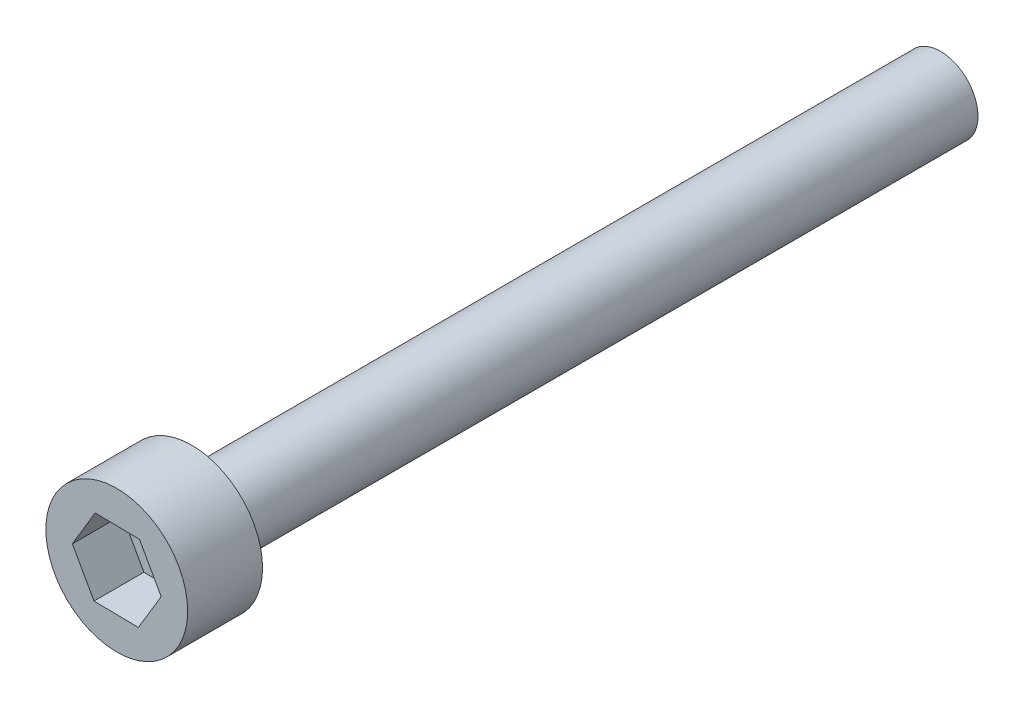
SolidWorks part; units mm, degrees
material "AISI 304"
ref_plane "前视基准面" through (0, 0, 0) normal (0, 0, 1) x (1, 0, 0)
ref_plane "上视基准面" through (0, 0, 0) normal (0, 1, 0) x (1, 0, 0)
ref_plane "右视基准面" through (0, 0, 0) normal (1, 0, 0) x (0, 0, -1)
sketch "草图1" plane through (0, 0, 0) normal (0, 0, 1) x (1, 0, 0)
  circle A0 centre (0, 0) radius 2.84
  dimension "D1" = 5.68
extrude "凸台-拉伸1" add sketch "草图1" along normal blind 3
sketch "草图2" plane through (0, 0, 0) normal (0, 0, -1) x (-1, 0, 0)
  circle A0 centre (0, 0) radius 1.5
  dimension "D1" = 3
extrude "凸台-拉伸2" add sketch "草图2" along normal blind 30
cosmetic thread "装饰螺纹线1" parameters "D2"=2
sketch "草图3" plane through (0, 0, 3) normal (0, 0, 1) x (1, 0, 0)
  line L1 (0.9126, 1.5262) -> (-0.8654, 1.5534)
  line L2 (-0.8654, 1.5534) -> (-1.778, 0.0272)
  line L3 (-1.778, 0.0272) -> (-0.9126, -1.5262)
  line L4 (-0.9126, -1.5262) -> (0.8654, -1.5534)
  line L5 (0.8654, -1.5534) -> (1.778, -0.0272)
  line L6 (1.778, -0.0272) -> (0.9126, 1.5262)
  circle A0 centre (0, 0) radius 1.54 construction
  dimension "D1" = 3.08
extrude "切除-拉伸1" cut sketch "草图3" against normal blind 2
